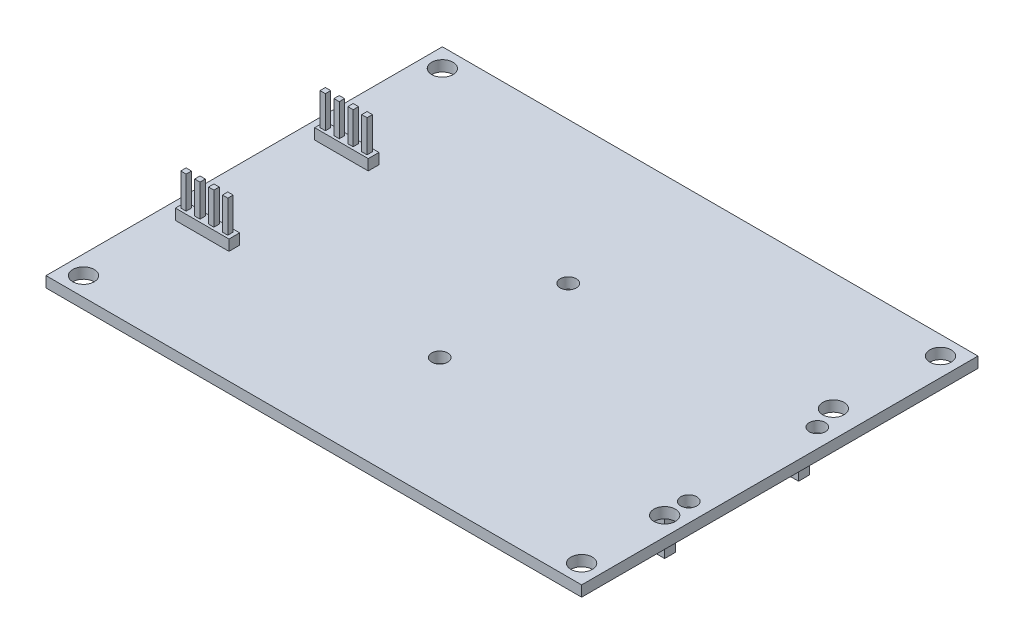
SolidWorks part; units mm, degrees
ref_plane "Front Plane" through (0, 0, 0) normal (0, 0, 1) x (1, 0, 0)
ref_plane "Top Plane" through (0, 0, 0) normal (0, 1, 0) x (1, 0, 0)
ref_plane "Right Plane" through (0, 0, 0) normal (1, 0, 0) x (0, 0, -1)
sketch "Sketch1" plane through (0, 0, 0) normal (0, 1, 0) x (1, 0, 0)
  line L0 (0, 13.6296) -> (0, 0) construction
  line L1 (50, -37) -> (-50, -37)
  line L2 (50, -37) -> (50, 37)
  line L3 (50, 37) -> (-50, 37)
  line L4 (-50, -37) -> (-50, 37)
  line L5 (50, -37) -> (-50, 37) construction
  line L6 (50, 37) -> (-50, -37) construction
  line L7 (0, 0) -> (15.083, 0) construction
  line L8 (0, -1.5) -> (15.083, -1.5) construction
  circle A0 centre (-46.5, 33.5) radius 2
  circle A1 centre (46.5, 33.5) radius 2
  circle A2 centre (46.5, -33.5) radius 2
  circle A3 centre (-46.5, -33.5) radius 2
  circle A4 centre (46.5, -18) radius 2
  circle A5 centre (45, 15) radius 2
  circle A6 centre (0, 10.5) radius 1.5
  circle A7 centre (46.5, 10.5) radius 1.5
  circle A8 centre (46.5, -13.5) radius 1.5
  circle A9 centre (0, -13.5) radius 1.5
  point P0 (0, 0)
  dimension "D5" = 4
  dimension "D8" = 4
  dimension "D9" = 4
  dimension "D14" = 3
  dimension "D15" = 3
  dimension "D1" = 100
  dimension "D2" = 74
  dimension "D3" = 3.5
  dimension "D4" = 3.5
  dimension "D6" = 15.5
  dimension "D7" = 18.5
  dimension "D10" = 5
  dimension "D11" = 3.5
  dimension "D12" = 50
  dimension "D13" = 26.5
  dimension "D16" = 3.5
  dimension "D17" = 12
extrude "Boss-Extrude1" add sketch "Sketch1" along normal blind 2
sketch "Sketch2" plane through (0, 2, 0) normal (0, 1, 0) x (1, 0, 0)
  line L0 (0, 0) -> (-50, 0) construction
  line L1 (-50, 37) -> (-50, -37) construction
  line L2 (-36.8395, -2) -> (-46.8395, -2) construction
  line L3 (-36.8395, 12) -> (-46.8395, 12)
  line L4 (-36.8395, 12) -> (-36.8395, 10)
  line L5 (-36.8395, 10) -> (-46.8395, 10)
  line L6 (-46.8395, 12) -> (-46.8395, 10)
  line L7 (-36.8395, 12) -> (-46.8395, 10) construction
  line L8 (-36.8395, 10) -> (-46.8395, 12) construction
  line L9 (50, 37) -> (-50, 37) construction
  line L10 (-36.8395, -14) -> (-46.8395, -14)
  line L11 (-46.8395, -16) -> (-46.8395, -14)
  line L12 (-36.8395, -16) -> (-46.8395, -16)
  line L13 (-36.8395, -16) -> (-36.8395, -14)
  point P5 (-41.8395, 11)
  dimension "D1" = 2
  dimension "D2" = 10
  dimension "D3" = 25
  dimension "D4" = 12
extrude "Boss-Extrude2" add sketch "Sketch2" along normal blind 2
sketch "Sketch3" plane through (0, 0, 0) normal (0, -1, 0) x (1, 0, 0)
  line L0 (-50, 37) -> (50, 37) construction
  line L1 (2.5, 15) -> (43.5, 15)
  line L2 (2.5, 15) -> (2.5, 13)
  line L3 (2.5, 13) -> (43.5, 13)
  line L4 (43.5, 15) -> (43.5, 13)
  line L5 (2.0022, 1.5) -> (39.822, 1.5) construction
  line L6 (50, 37) -> (50, -37) construction
  line L7 (2.5, 14) -> (43.5, 14) construction
  line L8 (4, 13.5) -> (3, 13.5)
  line L9 (4, 13.5) -> (4, 14.5)
  line L10 (4, 14.5) -> (3, 14.5)
  line L11 (3, 13.5) -> (3, 14.5)
  line L12 (4, 13.5) -> (3, 14.5) construction
  line L13 (4, 14.5) -> (3, 13.5) construction
  line L14 (6.5925, 13.5) -> (6.5925, 14.5)
  line L15 (6.5925, 13.5) -> (5.5925, 13.5)
  line L16 (5.5925, 13.5) -> (5.5925, 14.5)
  line L17 (6.5925, 14.5) -> (5.5925, 14.5)
  line L18 (9.185, 13.5) -> (9.185, 14.5)
  line L19 (9.185, 13.5) -> (8.185, 13.5)
  line L20 (8.185, 13.5) -> (8.185, 14.5)
  line L21 (9.185, 14.5) -> (8.185, 14.5)
  line L22 (11.7775, 13.5) -> (11.7775, 14.5)
  line L23 (11.7775, 13.5) -> (10.7775, 13.5)
  line L24 (10.7775, 13.5) -> (10.7775, 14.5)
  line L25 (11.7775, 14.5) -> (10.7775, 14.5)
  line L26 (14.37, 13.5) -> (14.37, 14.5)
  line L27 (14.37, 13.5) -> (13.37, 13.5)
  line L28 (13.37, 13.5) -> (13.37, 14.5)
  line L29 (14.37, 14.5) -> (13.37, 14.5)
  line L30 (16.9625, 13.5) -> (16.9625, 14.5)
  line L31 (16.9625, 13.5) -> (15.9625, 13.5)
  line L32 (15.9625, 13.5) -> (15.9625, 14.5)
  line L33 (16.9625, 14.5) -> (15.9625, 14.5)
  line L34 (19.555, 13.5) -> (19.555, 14.5)
  line L35 (19.555, 13.5) -> (18.555, 13.5)
  line L36 (18.555, 13.5) -> (18.555, 14.5)
  line L37 (19.555, 14.5) -> (18.555, 14.5)
  line L38 (22.1475, 13.5) -> (22.1475, 14.5)
  line L39 (22.1475, 13.5) -> (21.1475, 13.5)
  line L40 (21.1475, 13.5) -> (21.1475, 14.5)
  line L41 (22.1475, 14.5) -> (21.1475, 14.5)
  line L42 (24.74, 13.5) -> (24.74, 14.5)
  line L43 (24.74, 13.5) -> (23.74, 13.5)
  line L44 (23.74, 13.5) -> (23.74, 14.5)
  line L45 (24.74, 14.5) -> (23.74, 14.5)
  line L46 (27.3325, 13.5) -> (27.3325, 14.5)
  line L47 (27.3325, 13.5) -> (26.3325, 13.5)
  line L48 (26.3325, 13.5) -> (26.3325, 14.5)
  line L49 (27.3325, 14.5) -> (26.3325, 14.5)
  line L50 (29.925, 13.5) -> (29.925, 14.5)
  line L51 (29.925, 13.5) -> (28.925, 13.5)
  line L52 (28.925, 13.5) -> (28.925, 14.5)
  line L53 (29.925, 14.5) -> (28.925, 14.5)
  line L54 (32.5175, 13.5) -> (32.5175, 14.5)
  line L55 (32.5175, 13.5) -> (31.5175, 13.5)
  line L56 (31.5175, 13.5) -> (31.5175, 14.5)
  line L57 (32.5175, 14.5) -> (31.5175, 14.5)
  line L58 (35.11, 13.5) -> (35.11, 14.5)
  line L59 (35.11, 13.5) -> (34.11, 13.5)
  line L60 (34.11, 13.5) -> (34.11, 14.5)
  line L61 (35.11, 14.5) -> (34.11, 14.5)
  line L62 (37.7025, 13.5) -> (37.7025, 14.5)
  line L63 (37.7025, 13.5) -> (36.7025, 13.5)
  line L64 (36.7025, 13.5) -> (36.7025, 14.5)
  line L65 (37.7025, 14.5) -> (36.7025, 14.5)
  line L66 (40.295, 13.5) -> (40.295, 14.5)
  line L67 (40.295, 13.5) -> (39.295, 13.5)
  line L68 (39.295, 13.5) -> (39.295, 14.5)
  line L69 (40.295, 14.5) -> (39.295, 14.5)
  line L70 (42.8875, 13.5) -> (42.8875, 14.5)
  line L71 (42.8875, 13.5) -> (41.8875, 13.5)
  line L72 (41.8875, 13.5) -> (41.8875, 14.5)
  line L73 (42.8875, 14.5) -> (41.8875, 14.5)
  line L74 (4, -11.5) -> (3, -10.5) construction
  line L75 (4, -10.5) -> (3, -11.5) construction
  line L76 (2.5, -11) -> (43.5, -11) construction
  line L77 (42.8875, -11.5) -> (41.8875, -11.5)
  line L78 (41.8875, -10.5) -> (41.8875, -11.5)
  line L79 (42.8875, -10.5) -> (41.8875, -10.5)
  line L80 (42.8875, -10.5) -> (42.8875, -11.5)
  line L81 (40.295, -11.5) -> (39.295, -11.5)
  line L82 (39.295, -10.5) -> (39.295, -11.5)
  line L83 (40.295, -10.5) -> (39.295, -10.5)
  line L84 (40.295, -10.5) -> (40.295, -11.5)
  line L85 (37.7025, -11.5) -> (36.7025, -11.5)
  line L86 (36.7025, -10.5) -> (36.7025, -11.5)
  line L87 (37.7025, -10.5) -> (36.7025, -10.5)
  line L88 (37.7025, -10.5) -> (37.7025, -11.5)
  line L89 (35.11, -11.5) -> (34.11, -11.5)
  line L90 (34.11, -10.5) -> (34.11, -11.5)
  line L91 (35.11, -10.5) -> (34.11, -10.5)
  line L92 (35.11, -10.5) -> (35.11, -11.5)
  line L93 (32.5175, -11.5) -> (31.5175, -11.5)
  line L94 (31.5175, -10.5) -> (31.5175, -11.5)
  line L95 (32.5175, -10.5) -> (31.5175, -10.5)
  line L96 (32.5175, -10.5) -> (32.5175, -11.5)
  line L97 (29.925, -11.5) -> (28.925, -11.5)
  line L98 (28.925, -10.5) -> (28.925, -11.5)
  line L99 (29.925, -10.5) -> (28.925, -10.5)
  line L100 (29.925, -10.5) -> (29.925, -11.5)
  line L101 (27.3325, -11.5) -> (26.3325, -11.5)
  line L102 (26.3325, -10.5) -> (26.3325, -11.5)
  line L103 (27.3325, -10.5) -> (26.3325, -10.5)
  line L104 (27.3325, -10.5) -> (27.3325, -11.5)
  line L105 (24.74, -11.5) -> (23.74, -11.5)
  line L106 (23.74, -10.5) -> (23.74, -11.5)
  line L107 (24.74, -10.5) -> (23.74, -10.5)
  line L108 (24.74, -10.5) -> (24.74, -11.5)
  line L109 (22.1475, -11.5) -> (21.1475, -11.5)
  line L110 (21.1475, -10.5) -> (21.1475, -11.5)
  line L111 (22.1475, -10.5) -> (21.1475, -10.5)
  line L112 (22.1475, -10.5) -> (22.1475, -11.5)
  line L113 (19.555, -11.5) -> (18.555, -11.5)
  line L114 (18.555, -10.5) -> (18.555, -11.5)
  line L115 (19.555, -10.5) -> (18.555, -10.5)
  line L116 (19.555, -10.5) -> (19.555, -11.5)
  line L117 (16.9625, -11.5) -> (15.9625, -11.5)
  line L118 (15.9625, -10.5) -> (15.9625, -11.5)
  line L119 (16.9625, -10.5) -> (15.9625, -10.5)
  line L120 (16.9625, -10.5) -> (16.9625, -11.5)
  line L121 (14.37, -11.5) -> (13.37, -11.5)
  line L122 (13.37, -10.5) -> (13.37, -11.5)
  line L123 (14.37, -10.5) -> (13.37, -10.5)
  line L124 (14.37, -10.5) -> (14.37, -11.5)
  line L125 (11.7775, -11.5) -> (10.7775, -11.5)
  line L126 (10.7775, -10.5) -> (10.7775, -11.5)
  line L127 (11.7775, -10.5) -> (10.7775, -10.5)
  line L128 (11.7775, -10.5) -> (11.7775, -11.5)
  line L129 (9.185, -11.5) -> (8.185, -11.5)
  line L130 (8.185, -10.5) -> (8.185, -11.5)
  line L131 (9.185, -10.5) -> (8.185, -10.5)
  line L132 (9.185, -10.5) -> (9.185, -11.5)
  line L133 (6.5925, -11.5) -> (5.5925, -11.5)
  line L134 (5.5925, -10.5) -> (5.5925, -11.5)
  line L135 (6.5925, -10.5) -> (5.5925, -10.5)
  line L136 (6.5925, -10.5) -> (6.5925, -11.5)
  line L137 (3, -10.5) -> (3, -11.5)
  line L138 (4, -11.5) -> (3, -11.5)
  line L139 (4, -10.5) -> (4, -11.5)
  line L140 (4, -10.5) -> (3, -10.5)
  line L141 (43.5, -12) -> (43.5, -10)
  line L142 (2.5, -10) -> (43.5, -10)
  line L143 (2.5, -12) -> (2.5, -10)
  line L144 (2.5, -12) -> (43.5, -12)
  point P10 (3.5, 14)
  point P147 (3.5, -11)
  dimension "D1" = 2
  dimension "D2" = 41
  dimension "D3" = 22
  dimension "D4" = 11.5
  dimension "D5" = 6.5
  dimension "D6" = 1
  dimension "D7" = 1
  dimension "D8" = 0.5
extrude "Boss-Extrude4" add sketch "Sketch3" along normal blind 8
sketch "Sketch4" plane through (0, 2, 0) normal (0, 1, 0) x (1, 0, 0)
  line L0 (-46.8395, 11) -> (-36.8395, 11) construction
  line L1 (-46.8395, 12) -> (-46.8395, 10) construction
  line L2 (-36.8395, 10) -> (-36.8395, 12) construction
  line L3 (-46.8395, 12) -> (-46.8395, 10) construction
  line L4 (-46.3395, 10.5) -> (-45.3395, 10.5)
  line L5 (-46.3395, 10.5) -> (-46.3395, 11.5)
  line L6 (-46.3395, 11.5) -> (-45.3395, 11.5)
  line L7 (-45.3395, 10.5) -> (-45.3395, 11.5)
  line L8 (-46.3395, 10.5) -> (-45.3395, 11.5) construction
  line L9 (-46.3395, 11.5) -> (-45.3395, 10.5) construction
  line L10 (-43.747, 10.5) -> (-43.747, 11.5)
  line L11 (-43.747, 10.5) -> (-42.747, 10.5)
  line L12 (-42.747, 10.5) -> (-42.747, 11.5)
  line L13 (-43.747, 11.5) -> (-42.747, 11.5)
  line L14 (-41.1545, 10.5) -> (-41.1545, 11.5)
  line L15 (-41.1545, 10.5) -> (-40.1545, 10.5)
  line L16 (-40.1545, 10.5) -> (-40.1545, 11.5)
  line L17 (-41.1545, 11.5) -> (-40.1545, 11.5)
  line L18 (-38.562, 10.5) -> (-38.562, 11.5)
  line L19 (-38.562, 10.5) -> (-37.562, 10.5)
  line L20 (-37.562, 10.5) -> (-37.562, 11.5)
  line L21 (-38.562, 11.5) -> (-37.562, 11.5)
  line L22 (-46.8395, -2) -> (-35.8473, -2) construction
  line L23 (-36.8395, -14) -> (-46.8395, -14) construction
  line L24 (-46.8395, 10) -> (-36.8395, 10) construction
  line L25 (-46.3395, -15.5) -> (-45.3395, -14.5) construction
  line L26 (-46.3395, -14.5) -> (-45.3395, -15.5) construction
  line L27 (-46.8395, -15) -> (-36.8395, -15) construction
  line L28 (-38.562, -15.5) -> (-37.562, -15.5)
  line L29 (-37.562, -14.5) -> (-37.562, -15.5)
  line L30 (-38.562, -14.5) -> (-37.562, -14.5)
  line L31 (-38.562, -14.5) -> (-38.562, -15.5)
  line L32 (-41.1545, -15.5) -> (-40.1545, -15.5)
  line L33 (-40.1545, -14.5) -> (-40.1545, -15.5)
  line L34 (-41.1545, -14.5) -> (-40.1545, -14.5)
  line L35 (-41.1545, -14.5) -> (-41.1545, -15.5)
  line L36 (-43.747, -15.5) -> (-42.747, -15.5)
  line L37 (-42.747, -14.5) -> (-42.747, -15.5)
  line L38 (-43.747, -14.5) -> (-42.747, -14.5)
  line L39 (-43.747, -14.5) -> (-43.747, -15.5)
  line L40 (-45.3395, -14.5) -> (-45.3395, -15.5)
  line L41 (-46.3395, -15.5) -> (-45.3395, -15.5)
  line L42 (-46.3395, -14.5) -> (-46.3395, -15.5)
  line L43 (-46.3395, -14.5) -> (-45.3395, -14.5)
  point P6 (-45.8395, 11)
  point P49 (-45.8395, -15)
  dimension "D1" = 1
  dimension "D2" = 1
  dimension "D3" = 0.5
extrude "Boss-Extrude5" add sketch "Sketch4" along normal blind 8
sketch "Sketch5" plane through (0, 2, 0) normal (0, 1, 0) x (1, 0, 0)
  line L0 (-50, 37) -> (-50, -37) construction
  line L1 (-50, -37) -> (50, -37) construction
  line L2 (50, 37) -> (-50, 37) construction
  line L3 (50, -37) -> (50, 37) construction
  line L4 (-46.8395, 12) -> (-46.8395, 10)
  line L5 (-46.8395, 10) -> (-36.8395, 10)
  line L6 (-36.8395, 10) -> (-36.8395, 12)
  line L7 (-36.8395, 12) -> (-46.8395, 12)
  line L8 (-46.8395, 12) -> (-46.8395, 10)
  line L9 (-46.8395, 10) -> (-36.8395, 10)
  line L10 (-36.8395, 10) -> (-36.8395, 12)
  line L11 (-36.8395, 12) -> (-46.8395, 12)
  line L12 (-36.8395, -16) -> (-36.8395, -14)
  line L13 (-36.8395, -14) -> (-46.8395, -14)
  line L14 (-46.8395, -14) -> (-46.8395, -16)
  line L15 (-46.8395, -16) -> (-36.8395, -16)
  line L16 (-36.8395, -16) -> (-36.8395, -14)
  line L17 (-36.8395, -14) -> (-46.8395, -14)
  line L18 (-46.8395, -14) -> (-46.8395, -16)
  line L19 (-46.8395, -16) -> (-36.8395, -16)
  line L20 (-50, 37) -> (-50, -37)
  line L21 (-50, -37) -> (50, -37)
  line L22 (50, 37) -> (-50, 37)
  line L23 (50, -37) -> (50, 37)
  circle A0 centre (46.5, -18) radius 2 construction
  circle A1 centre (46.5, -33.5) radius 2 construction
  circle A2 centre (45, 15) radius 2 construction
  circle A3 centre (46.5, 33.5) radius 2 construction
  circle A4 centre (-46.5, 33.5) radius 2 construction
  circle A5 centre (-46.5, -33.5) radius 2 construction
  circle A6 centre (46.5, -18) radius 2
  circle A7 centre (46.5, -33.5) radius 2
  circle A8 centre (45, 15) radius 2
  circle A9 centre (46.5, 33.5) radius 2
  circle A10 centre (-46.5, 33.5) radius 2
  circle A11 centre (-46.5, -33.5) radius 2
  dimension "D1" = 0
  dimension "D2" = 0
